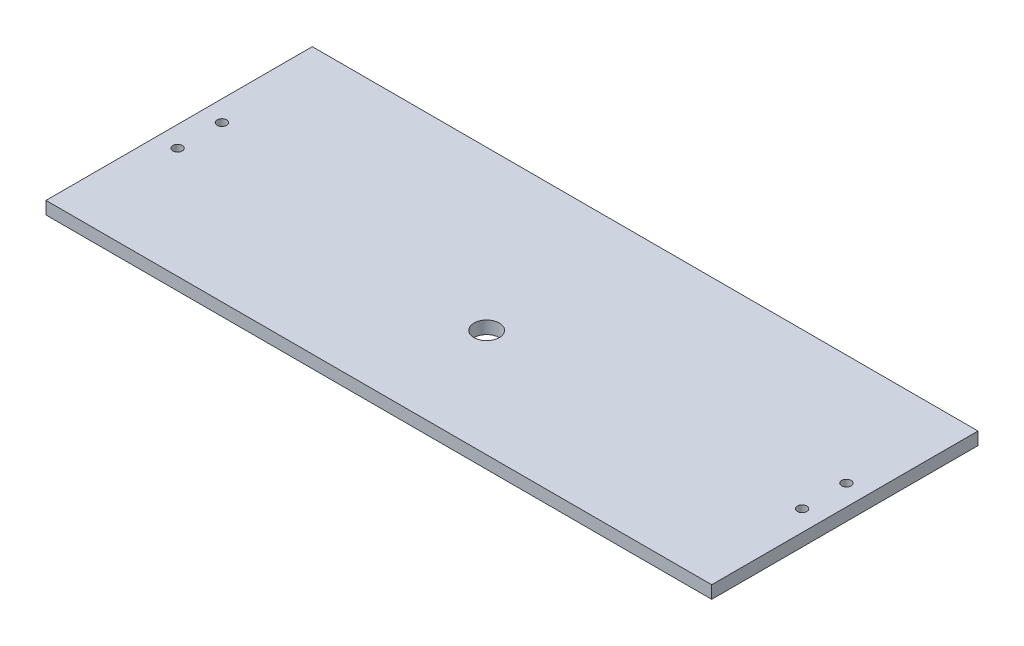
SolidWorks part; units mm, degrees
ref_plane "Alzado" through (0, 0, 0) normal (0, 0, 1) x (1, 0, 0)
ref_plane "Planta" through (0, 0, 0) normal (0, 1, 0) x (1, 0, 0)
ref_plane "Vista lateral" through (0, 0, 0) normal (1, 0, 0) x (0, 0, -1)
sketch "Croquis2" plane through (-13.7319, 703.6284, -26.3243) normal (0, -1, 0) x (-1, 0, 0)
  line L1 (-133.2303, 56.1152) -> (76.7697, 56.1152)
  line L2 (-133.2303, 56.1152) -> (-133.2303, -27.8848)
  line L3 (-133.2303, -27.8848) -> (76.7697, -27.8848)
  line L4 (76.7697, 56.1152) -> (76.7697, -27.8848)
  circle A0 centre (-28.2303, 6.1152) radius 4
  circle A1 centre (-126.7303, 7.1152) radius 1.5
  circle A2 centre (-126.7303, 21.1152) radius 1.5
  circle A3 centre (70.2697, 21.1152) radius 1.5
  circle A4 centre (70.2697, 7.1152) radius 1.5
extrude "Saliente-Extruir1" add sketch "Croquis2" against normal blind 4
